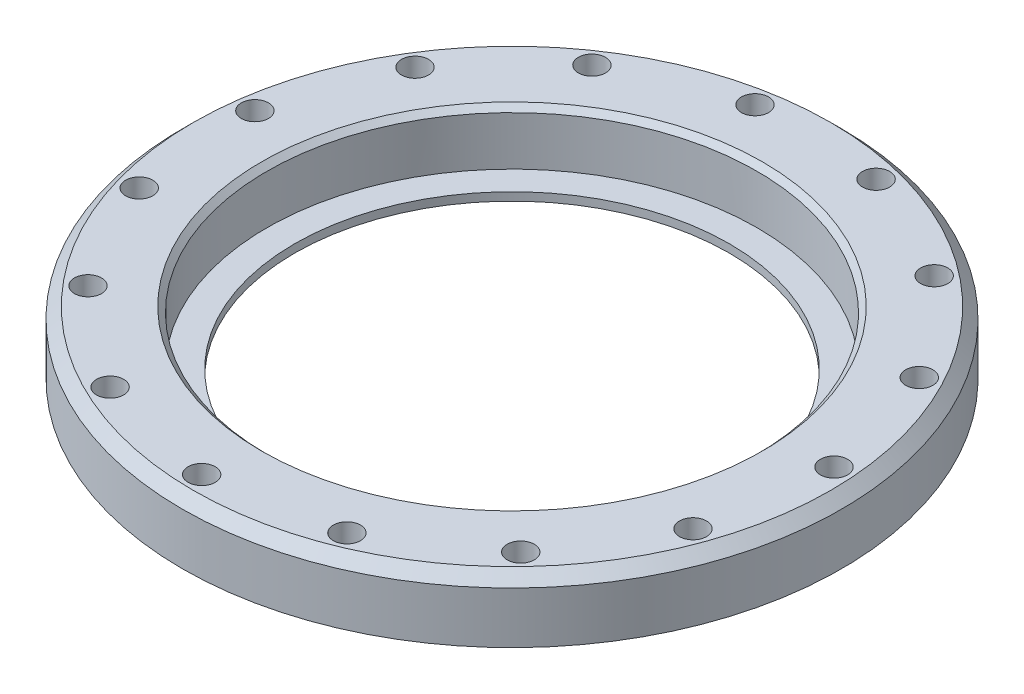
SolidWorks part; units mm, degrees
ref_plane "Front Plane" through (0, 0, 0) normal (0, 0, 1) x (1, 0, 0)
ref_plane "Top Plane" through (0, 0, 0) normal (0, 1, 0) x (1, 0, 0)
ref_plane "Right Plane" through (0, 0, 0) normal (1, 0, 0) x (0, 0, -1)
sketch "Sketch1" plane through (0, 0, 0) normal (0, 1, 0) x (1, 0, 0)
  arc A0 (-50.0812, 1.3713) -> (-50.0812, -1.3713) centre (0, 0) ccw
  arc A1 (2.0496, 50.0581) -> (-2.0496, 50.0581) centre (0, 50.1) ccw
  arc A2 (8.8467, 49.3127) -> (4.7858, 49.8709) centre (6.8219, 49.6334) ccw
  arc A3 (15.4791, 47.6488) -> (11.5319, 48.7547) centre (13.5168, 48.2422) ccw
  arc A4 (21.8231, 45.0973) -> (18.0633, 46.7304) centre (19.9599, 45.9523) ccw
  arc A5 (27.7606, 41.7057) -> (24.2582, 43.8355) centre (26.0312, 42.8064) ccw
  arc A6 (33.1809, 37.5371) -> (30.0012, 40.1241) centre (31.6175, 38.8631) ccw
  arc A7 (37.9832, 32.6694) -> (35.1853, 35.6652) centre (36.6149, 34.1959) ccw
  arc A8 (42.0779, 27.1931) -> (39.714, 30.5419) centre (40.9302, 28.8917) ccw
  arc A9 (45.3887, 21.2102) -> (43.5029, 24.8497) centre (44.483, 23.0493) ccw
  arc A10 (47.8541, 14.8322) -> (46.4814, 18.6947) centre (47.2073, 16.7775) ccw
  arc A11 (49.428, 8.1779) -> (48.5941, 12.1913) centre (49.0521, 10.1931) ccw
  arc A12 (50.0812, 1.3713) -> (49.8015, 5.4609) centre (49.9832, 3.4189) ccw
  arc A13 (49.8015, -5.4609) -> (50.0812, -1.3713) centre (49.9832, -3.4189) ccw
  arc A14 (48.5941, -12.1913) -> (49.428, -8.1779) centre (49.0521, -10.1931) ccw
  arc A15 (46.4814, -18.6947) -> (47.8541, -14.8322) centre (47.2073, -16.7775) ccw
  arc A16 (43.5029, -24.8497) -> (45.3887, -21.2102) centre (44.483, -23.0493) ccw
  arc A17 (39.714, -30.5419) -> (42.0779, -27.1931) centre (40.9302, -28.8917) ccw
  arc A18 (35.1853, -35.6652) -> (37.9832, -32.6694) centre (36.6149, -34.1959) ccw
  arc A19 (30.0012, -40.1241) -> (33.1809, -37.5371) centre (31.6175, -38.8631) ccw
  arc A20 (24.2582, -43.8355) -> (27.7606, -41.7057) centre (26.0312, -42.8064) ccw
  arc A21 (18.0633, -46.7304) -> (21.8231, -45.0973) centre (19.9599, -45.9523) ccw
  arc A22 (11.5319, -48.7547) -> (15.4791, -47.6488) centre (13.5168, -48.2422) ccw
  arc A23 (4.7858, -49.8709) -> (8.8467, -49.3127) centre (6.8219, -49.6334) ccw
  arc A24 (-2.0496, -50.0581) -> (2.0496, -50.0581) centre (0, -50.1) ccw
  arc A25 (-8.8467, -49.3127) -> (-4.7858, -49.8709) centre (-6.8219, -49.6334) ccw
  arc A26 (-15.4791, -47.6488) -> (-11.5319, -48.7547) centre (-13.5168, -48.2422) ccw
  arc A27 (-21.8231, -45.0973) -> (-18.0633, -46.7304) centre (-19.9599, -45.9523) ccw
  arc A28 (-27.7606, -41.7057) -> (-24.2582, -43.8355) centre (-26.0312, -42.8064) ccw
  arc A29 (-33.1809, -37.5371) -> (-30.0012, -40.1241) centre (-31.6175, -38.8631) ccw
  arc A30 (-37.9832, -32.6694) -> (-35.1853, -35.6652) centre (-36.6149, -34.1959) ccw
  arc A31 (-42.0779, -27.1931) -> (-39.714, -30.5419) centre (-40.9302, -28.8917) ccw
  arc A32 (-45.3887, -21.2102) -> (-43.5029, -24.8497) centre (-44.483, -23.0493) ccw
  arc A33 (-47.8541, -14.8322) -> (-46.4814, -18.6947) centre (-47.2073, -16.7775) ccw
  arc A34 (-49.428, -8.1779) -> (-48.5941, -12.1913) centre (-49.0521, -10.1931) ccw
  arc A35 (-50.0812, -1.3713) -> (-49.8015, -5.4609) centre (-49.9832, -3.4189) ccw
  arc A36 (-49.8015, 5.4609) -> (-50.0812, 1.3713) centre (-49.9832, 3.4189) ccw
  arc A37 (-48.5941, 12.1913) -> (-49.428, 8.1779) centre (-49.0521, 10.1931) ccw
  arc A38 (-46.4814, 18.6947) -> (-47.8541, 14.8322) centre (-47.2073, 16.7775) ccw
  arc A39 (-43.5029, 24.8497) -> (-45.3887, 21.2102) centre (-44.483, 23.0493) ccw
  arc A40 (-39.714, 30.5419) -> (-42.0779, 27.1931) centre (-40.9302, 28.8917) ccw
  arc A41 (-35.1853, 35.6652) -> (-37.9832, 32.6694) centre (-36.6149, 34.1959) ccw
  arc A42 (-30.0012, 40.1241) -> (-33.1809, 37.5371) centre (-31.6175, 38.8631) ccw
  arc A43 (-24.2582, 43.8355) -> (-27.7606, 41.7057) centre (-26.0312, 42.8064) ccw
  arc A44 (-18.0633, 46.7304) -> (-21.8231, 45.0973) centre (-19.9599, 45.9523) ccw
  arc A45 (-11.5319, 48.7547) -> (-15.4791, 47.6488) centre (-13.5168, 48.2422) ccw
  arc A46 (-4.7858, 49.8709) -> (-8.8467, 49.3127) centre (-6.8219, 49.6334) ccw
  circle A47 centre (0, 0) radius 60.65
  circle A48 centre (0, 0) radius 56.65 construction
  circle A49 centre (0, 56.65) radius 2.625 construction
  circle A50 centre (0, 0) radius 45
  circle A51 centre (0, 0) radius 40
  arc A52 (-49.428, 8.1779) -> (-49.8015, 5.4609) centre (0, 0) ccw
  arc A53 (-47.8541, 14.8322) -> (-48.5941, 12.1913) centre (0, 0) ccw
  arc A54 (-45.3887, 21.2102) -> (-46.4814, 18.6947) centre (0, 0) ccw
  arc A55 (-42.0779, 27.1931) -> (-43.5029, 24.8497) centre (0, 0) ccw
  arc A56 (-37.9832, 32.6694) -> (-39.714, 30.5419) centre (0, 0) ccw
  arc A57 (-33.1809, 37.5371) -> (-35.1853, 35.6652) centre (0, 0) ccw
  arc A58 (-27.7606, 41.7057) -> (-30.0012, 40.1241) centre (0, 0) ccw
  arc A59 (-21.8231, 45.0973) -> (-24.2582, 43.8355) centre (0, 0) ccw
  arc A60 (-15.4791, 47.6488) -> (-18.0633, 46.7304) centre (0, 0) ccw
  arc A61 (-8.8467, 49.3127) -> (-11.5319, 48.7547) centre (0, 0) ccw
  arc A62 (-2.0496, 50.0581) -> (-4.7858, 49.8709) centre (0, 0) ccw
  arc A63 (4.7858, 49.8709) -> (2.0496, 50.0581) centre (0, 0) ccw
  arc A64 (11.5319, 48.7547) -> (8.8467, 49.3127) centre (0, 0) ccw
  arc A65 (18.0633, 46.7304) -> (15.4791, 47.6488) centre (0, 0) ccw
  arc A66 (24.2582, 43.8355) -> (21.8231, 45.0973) centre (0, 0) ccw
  arc A67 (30.0012, 40.1241) -> (27.7606, 41.7057) centre (0, 0) ccw
  arc A68 (35.1853, 35.6652) -> (33.1809, 37.5371) centre (0, 0) ccw
  arc A69 (39.714, 30.5419) -> (37.9832, 32.6694) centre (0, 0) ccw
  arc A70 (43.5029, 24.8497) -> (42.0779, 27.1931) centre (0, 0) ccw
  arc A71 (46.4814, 18.6947) -> (45.3887, 21.2102) centre (0, 0) ccw
  arc A72 (48.5941, 12.1913) -> (47.8541, 14.8322) centre (0, 0) ccw
  arc A73 (49.8015, 5.4609) -> (49.428, 8.1779) centre (0, 0) ccw
  arc A74 (50.0812, -1.3713) -> (50.0812, 1.3713) centre (0, 0) ccw
  arc A75 (49.428, -8.1779) -> (49.8015, -5.4609) centre (0, 0) ccw
  arc A76 (47.8541, -14.8322) -> (48.5941, -12.1913) centre (0, 0) ccw
  arc A77 (45.3887, -21.2102) -> (46.4814, -18.6947) centre (0, 0) ccw
  arc A78 (42.0779, -27.1931) -> (43.5029, -24.8497) centre (0, 0) ccw
  arc A79 (37.9832, -32.6694) -> (39.714, -30.5419) centre (0, 0) ccw
  arc A80 (33.1809, -37.5371) -> (35.1853, -35.6652) centre (0, 0) ccw
  arc A81 (27.7606, -41.7057) -> (30.0012, -40.1241) centre (0, 0) ccw
  arc A82 (21.8231, -45.0973) -> (24.2582, -43.8355) centre (0, 0) ccw
  arc A83 (15.4791, -47.6488) -> (18.0633, -46.7304) centre (0, 0) ccw
  arc A84 (8.8467, -49.3127) -> (11.5319, -48.7547) centre (0, 0) ccw
  arc A85 (2.0496, -50.0581) -> (4.7858, -49.8709) centre (0, 0) ccw
  arc A86 (-4.7858, -49.8709) -> (-2.0496, -50.0581) centre (0, 0) ccw
  arc A87 (-11.5319, -48.7547) -> (-8.8467, -49.3127) centre (0, 0) ccw
  arc A88 (-18.0633, -46.7304) -> (-15.4791, -47.6488) centre (0, 0) ccw
  arc A89 (-24.2582, -43.8355) -> (-21.8231, -45.0973) centre (0, 0) ccw
  arc A90 (-30.0012, -40.1241) -> (-27.7606, -41.7057) centre (0, 0) ccw
  arc A91 (-35.1853, -35.6652) -> (-33.1809, -37.5371) centre (0, 0) ccw
  arc A92 (-39.714, -30.5419) -> (-37.9832, -32.6694) centre (0, 0) ccw
  arc A93 (-43.5029, -24.8497) -> (-42.0779, -27.1931) centre (0, 0) ccw
  arc A94 (-46.4814, -18.6947) -> (-45.3887, -21.2102) centre (0, 0) ccw
  arc A95 (-48.5941, -12.1913) -> (-47.8541, -14.8322) centre (0, 0) ccw
  arc A96 (-49.8015, -5.4609) -> (-49.428, -8.1779) centre (0, 0) ccw
  dimension "D1" = 100.2
  dimension "D2" = 4.1
  dimension "D3" = 46
  dimension "D4" = 10.55
  dimension "D5" = 4
  dimension "D6" = 5.25
  dimension "D7" = 90
  dimension "D8" = 80
extrude "Boss-Extrude1" add sketch "Sketch1" along normal blind 11 contours A47 A96 A35 A0 A36 A52 A37 A53 A38 A54 A39 A55 A40 A56 A41 A57 A42 A58 A43 A59 A44 A60 A45 A61 A46 A62 A1 A63 A2 A64 A3 A65 A4 A66 A5 A67 A6 A68 A7 A69 A8 A70 A9 A71 A10 A72 A11 A73 A12 A74
sketch "Sketch2" plane through (0, 11, 0) normal (0, 1, 0) x (1, 0, 0)
  circle A0 centre (0, 0) radius 45.1
  circle A1 centre (0, 0) radius 60.65
  circle A2 centre (0, 0) radius 60.65 construction
  dimension "D1" = 90.2
extrude "Boss-Extrude2" add sketch "Sketch2" against normal blind 11.5 contours A0
sketch "Sketch3" plane through (0, -0.5, 0) normal (0, -1, 0) x (1, 0, 0)
  circle A0 centre (0, 0) radius 40
  circle A1 centre (0, 0) radius 45.1
  circle A2 centre (0, 0) radius 45.1 construction
  dimension "D1" = 80
extrude "Boss-Extrude3" add sketch "Sketch3" against normal blind 1.5
chamfer "Chamfer1" distance 1 angle 45 1 edges at (0, 11, 45.1)
sketch "Sketch4" plane through (0, -0.5, 0) normal (0, -1, 0) x (1, 0, 0)
sketch "Sketch5" plane through (0, -0.5, 0) normal (0, -1, 0) x (1, 0, 0)
  circle A0 centre (13.2333, -53.7705) radius 2.5 construction
  circle A1 centre (13.2333, -53.7705) radius 2.5
extrude "Cut-Extrude2" cut sketch "Sketch5" against normal through all both and the other way through all
sketch "Sketch6" plane through (0, -0.5, 0) normal (0, -1, 0) x (1, 0, 0)
  circle A0 centre (0, 0) radius 50.1 construction
  circle A1 centre (0, 50.1) radius 2.05 construction
  arc A2 (2.0496, 50.0581) -> (-2.0496, 50.0581) centre (0, 50.1) ccw construction
  circle A3 centre (6.8219, 49.6334) radius 2.05 construction
  circle A4 centre (13.5168, 48.2422) radius 2.05 construction
  circle A5 centre (19.9599, 45.9523) radius 2.05 construction
  circle A6 centre (26.0312, 42.8064) radius 2.05 construction
  circle A7 centre (31.6175, 38.8631) radius 2.05 construction
  circle A8 centre (36.6149, 34.1959) radius 2.05 construction
  circle A9 centre (40.9302, 28.8917) radius 2.05 construction
  circle A10 centre (44.483, 23.0493) radius 2.05 construction
  circle A11 centre (47.2073, 16.7775) radius 2.05 construction
  circle A12 centre (49.0521, 10.1931) radius 2.05 construction
  circle A13 centre (49.9832, 3.4189) radius 2.05 construction
  circle A14 centre (49.9832, -3.4189) radius 2.05 construction
  circle A15 centre (49.0521, -10.1931) radius 2.05 construction
  circle A16 centre (47.2073, -16.7775) radius 2.05 construction
  circle A17 centre (44.483, -23.0493) radius 2.05 construction
  circle A18 centre (40.9302, -28.8917) radius 2.05 construction
  circle A19 centre (36.6149, -34.1959) radius 2.05 construction
  circle A20 centre (31.6175, -38.8631) radius 2.05 construction
  circle A21 centre (26.0312, -42.8064) radius 2.05 construction
  circle A22 centre (19.9599, -45.9523) radius 2.05 construction
  circle A23 centre (13.5168, -48.2422) radius 2.05 construction
  circle A24 centre (6.8219, -49.6334) radius 2.05 construction
  circle A25 centre (0, -50.1) radius 2.05 construction
  circle A26 centre (-6.8219, -49.6334) radius 2.05 construction
  circle A27 centre (-13.5168, -48.2422) radius 2.05 construction
  circle A28 centre (-19.9599, -45.9523) radius 2.05 construction
  circle A29 centre (-26.0312, -42.8064) radius 2.05 construction
  circle A30 centre (-31.6175, -38.8631) radius 2.05 construction
  circle A31 centre (-36.6149, -34.1959) radius 2.05 construction
  circle A32 centre (-40.9302, -28.8917) radius 2.05 construction
  circle A33 centre (-44.483, -23.0493) radius 2.05 construction
  circle A34 centre (-47.2073, -16.7775) radius 2.05 construction
  circle A35 centre (-49.0521, -10.1931) radius 2.05 construction
  circle A36 centre (-49.9832, -3.4189) radius 2.05 construction
  circle A37 centre (-49.9832, 3.4189) radius 2.05 construction
  circle A38 centre (-49.0521, 10.1931) radius 2.05 construction
  circle A39 centre (-47.2073, 16.7775) radius 2.05 construction
  circle A40 centre (-44.483, 23.0493) radius 2.05 construction
  circle A41 centre (-40.9302, 28.8917) radius 2.05 construction
  circle A42 centre (-36.6149, 34.1959) radius 2.05 construction
  circle A43 centre (-31.6175, 38.8631) radius 2.05 construction
  circle A44 centre (-26.0312, 42.8064) radius 2.05 construction
  circle A45 centre (-19.9599, 45.9523) radius 2.05 construction
  circle A46 centre (-13.5168, 48.2422) radius 2.05 construction
  circle A47 centre (-6.8219, 49.6334) radius 2.05 construction
  circle A49 centre (0, -50.1) radius 2.15
  circle A50 centre (-6.8219, -49.6334) radius 2.15
  circle A51 centre (-13.5168, -48.2422) radius 2.15
  circle A52 centre (-19.9599, -45.9523) radius 2.15
  circle A53 centre (-26.0312, -42.8064) radius 2.15
  circle A54 centre (-31.6175, -38.8631) radius 2.15
  circle A55 centre (-36.6149, -34.1959) radius 2.15
  circle A56 centre (-40.9302, -28.8917) radius 2.15
  circle A57 centre (-44.483, -23.0493) radius 2.15
  circle A58 centre (-47.2073, -16.7775) radius 2.15
  circle A59 centre (-49.0521, -10.1931) radius 2.15
  circle A60 centre (-49.9832, -3.4189) radius 2.15
  circle A61 centre (-49.9832, 3.4189) radius 2.15
  circle A62 centre (-49.0521, 10.1931) radius 2.15
  circle A63 centre (-47.2073, 16.7775) radius 2.15
  circle A64 centre (-44.483, 23.0493) radius 2.15
  circle A65 centre (-40.9302, 28.8917) radius 2.15
  circle A66 centre (-36.6149, 34.1959) radius 2.15
  circle A67 centre (-31.6175, 38.8631) radius 2.15
  circle A68 centre (-26.0312, 42.8064) radius 2.15
  circle A69 centre (-19.9599, 45.9523) radius 2.15
  circle A70 centre (-13.5168, 48.2422) radius 2.15
  circle A71 centre (-6.8219, 49.6334) radius 2.15
  circle A72 centre (0, 50.1) radius 2.15
  circle A73 centre (6.8219, 49.6334) radius 2.15
  circle A74 centre (13.5168, 48.2422) radius 2.15
  circle A75 centre (19.9599, 45.9523) radius 2.15
  circle A76 centre (26.0312, 42.8064) radius 2.15
  circle A77 centre (31.6175, 38.8631) radius 2.15
  circle A78 centre (36.6149, 34.1959) radius 2.15
  circle A79 centre (40.9302, 28.8917) radius 2.15
  circle A80 centre (44.483, 23.0493) radius 2.15
  circle A81 centre (47.2073, 16.7775) radius 2.15
  circle A82 centre (49.0521, 10.1931) radius 2.15
  circle A83 centre (49.9832, 3.4189) radius 2.15
  circle A84 centre (49.9832, -3.4189) radius 2.15
  circle A85 centre (49.0521, -10.1931) radius 2.15
  circle A86 centre (47.2073, -16.7775) radius 2.15
  circle A87 centre (44.483, -23.0493) radius 2.15
  circle A88 centre (40.9302, -28.8917) radius 2.15
  circle A89 centre (36.6149, -34.1959) radius 2.15
  circle A90 centre (31.6175, -38.8631) radius 2.15
  circle A91 centre (26.0312, -42.8064) radius 2.15
  circle A92 centre (19.9599, -45.9523) radius 2.15
  circle A93 centre (13.5168, -48.2422) radius 2.15
  circle A94 centre (6.8219, -49.6334) radius 2.15
  point P101 (0, 0)
  point P194 (0, 0)
  dimension "D1" = 46
  dimension "D2" = 0.1
  dimension "D3" = 46
extrude "Cut-Extrude3" cut sketch "Sketch6" against normal blind 10
chamfer "Chamfer3" distance 0.5 angle 45 46 edges at (-26.0312, -0.5, -44.9564) (-31.6175, -0.5, -41.0131) (-36.6149, -0.5, -36.3459) (-40.9302, -0.5, -31.0417) (-44.483, -0.5, -25.1993) (-47.2073, -0.5, -18.9275) (-49.0521, -0.5, -12.3431) (-49.9832, -0.5, -5.5689) (-49.9832, -0.5, 1.2689) (-49.0521, -0.5, 8.0431) (-47.2073, -0.5, 14.6275) (-44.483, -0.5, 20.8993) (-40.9302, -0.5, 26.7417) (-36.6149, -0.5, 32.0459) (-31.6175, -0.5, 36.7131) (-26.0312, -0.5, 40.6564) (-19.9599, -0.5, 43.8023) (-13.5168, -0.5, 46.0922) (-6.8219, -0.5, 47.4834) (0, -0.5, 47.95) (6.8219, -0.5, 47.4834) (13.5168, -0.5, 46.0922) (19.9599, -0.5, 43.8023) (26.0312, -0.5, 40.6564) (31.6175, -0.5, 36.7131) (36.6149, -0.5, 32.0459) (40.9302, -0.5, 26.7417) (44.483, -0.5, 20.8993) (47.2073, -0.5, 14.6275) (49.0521, -0.5, 8.0431) (49.9832, -0.5, 1.2689) (49.9832, -0.5, -5.5689) (49.0521, -0.5, -12.3431) (47.2073, -0.5, -18.9275) (44.483, -0.5, -25.1993) (40.9302, -0.5, -31.0417) (36.6149, -0.5, -36.3459) (31.6175, -0.5, -41.0131) (26.0312, -0.5, -44.9564) (19.9599, -0.5, -48.1023) (13.5168, -0.5, -50.3922) (6.8219, -0.5, -51.7834) (0, -0.5, -52.25) (-6.8219, -0.5, -51.7834) (-13.5168, -0.5, -50.3922) (-19.9599, -0.5, -48.1023)
pattern_circular "CirPattern6" count 15 over 360 about axis through (0, 0, 0) along (0, 1, 0) of "Cut-Extrude2"
chamfer "Chamfer4" distance 2 angle 45 1 edges at (0, 11, 60.65)
